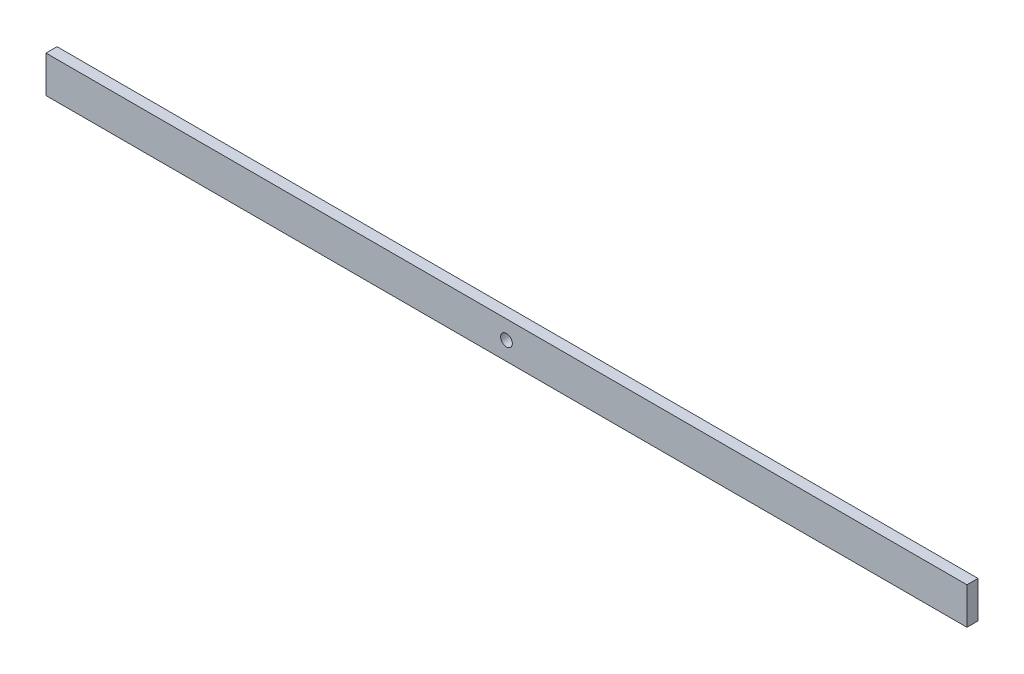
SolidWorks part; units mm, degrees
ref_plane "Front Plane" through (0, 0, 0) normal (0, 0, 1) x (1, 0, 0)
ref_plane "Top Plane" through (0, 0, 0) normal (0, 1, 0) x (1, 0, 0)
ref_plane "Right Plane" through (0, 0, 0) normal (1, 0, 0) x (0, 0, -1)
sketch "Sketch1" plane through (0, 0, 0) normal (0, 0, 1) x (1, 0, 0)
  line L1 (-125, 5) -> (125, 5)
  line L2 (-125, 5) -> (-125, -5)
  line L3 (-125, -5) -> (125, -5)
  line L4 (125, 5) -> (125, -5)
  line L5 (-125, 5) -> (125, -5) construction
  line L6 (-125, -5) -> (125, 5) construction
  circle A0 centre (0, 0) radius 1.585
  point P0 (0, 0)
  dimension "D3" = 3.17
  dimension "D1" = 250
  dimension "D2" = 10
extrude "Boss-Extrude1" add sketch "Sketch1" along normal blind 3
